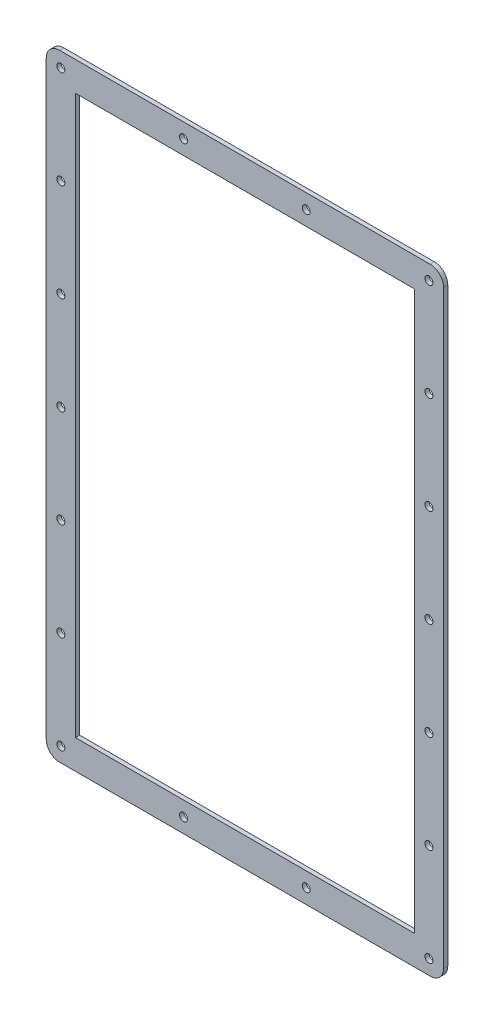
SolidWorks part; units mm, degrees
material "EPDM 60 Durometer"
ref_plane "Front Plane" through (0, 0, 0) normal (0, 0, 1) x (1, 0, 0)
ref_plane "Top Plane" through (0, 0, 0) normal (0, 1, 0) x (1, 0, 0)
ref_plane "Right Plane" through (0, 0, 0) normal (1, 0, 0) x (0, 0, -1)
sketch "Sketch1" plane through (0, 0, 0) normal (0, 0, 1) x (1, 0, 0)
  line L0 (-127.5, 210) -> (-127.5, -210)
  line L1 (-127.5, -210) -> (127.5, -210)
  line L2 (127.5, -210) -> (127.5, 210)
  line L3 (139.5, 232) -> (-139.5, 232)
  line L4 (-149.5, 222) -> (-149.5, -222)
  line L5 (-139.5, -232) -> (139.5, -232)
  line L6 (149.5, -222) -> (149.5, 222)
  line L7 (127.5, 210) -> (-127.5, 210)
  arc A0 (-139.5, 232) -> (-149.5, 222) centre (-139.5, 222) ccw
  arc A1 (-149.5, -222) -> (-139.5, -232) centre (-139.5, -222) ccw
  arc A2 (139.5, -232) -> (149.5, -222) centre (139.5, -222) ccw
  arc A3 (149.5, 222) -> (139.5, 232) centre (139.5, 222) ccw
  circle A4 centre (138.5, -221) radius 3
  circle A5 centre (46.1667, -221) radius 3
  circle A6 centre (-46.1667, -221) radius 3
  circle A7 centre (-138.5, -221) radius 3
  circle A8 centre (-138.5, -73.6667) radius 3
  circle A9 centre (-138.5, 0) radius 3
  circle A10 centre (138.5, -73.6667) radius 3
  circle A11 centre (138.5, 0) radius 3
  circle A12 centre (138.5, 73.6667) radius 3
  circle A13 centre (138.5, 147.3333) radius 3
  circle A14 centre (138.5, 221) radius 3
  circle A15 centre (46.1667, 221) radius 3
  circle A16 centre (-138.5, 73.6667) radius 3
  circle A17 centre (-138.5, 147.3333) radius 3
  circle A18 centre (-46.1667, 221) radius 3
  circle A19 centre (-138.5, 221) radius 3
  circle A20 centre (138.5, -147.3333) radius 3
  circle A21 centre (-138.5, -147.3333) radius 3
  dimension "D5" = 10
  dimension "D6" = 6
  dimension "D1" = 420
  dimension "D2" = 255
  dimension "D3" = 464
  dimension "D4" = 299
  dimension "D7" = 92.3333
  dimension "D8" = 73.6667
extrude "Boss-Extrude1" add sketch "Sketch1" along normal blind 3.175
